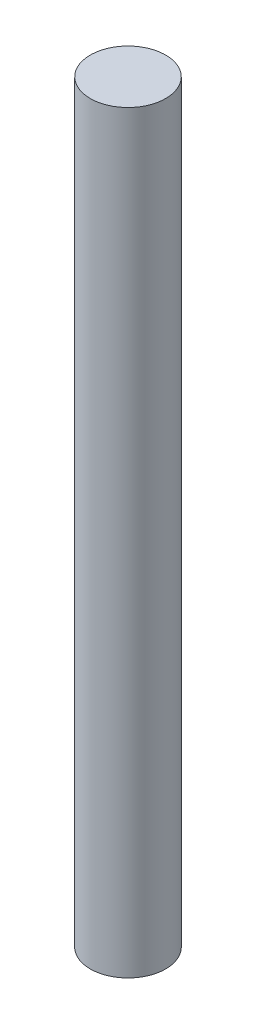
SolidWorks part; units mm, degrees
ref_plane "Alzado" through (0, 0, 0) normal (0, 0, 1) x (1, 0, 0)
ref_plane "Planta" through (0, 0, 0) normal (0, 1, 0) x (1, 0, 0)
ref_plane "Vista lateral" through (0, 0, 0) normal (1, 0, 0) x (0, 0, -1)
sketch "Croquis1" plane through (0, 0, 0) normal (0, 1, 0) x (1, 0, 0)
  circle A0 centre (0, 0) radius 2.5
  dimension "D1" = 5
extrude "Saliente-Extruir1" add sketch "Croquis1" along normal blind 50
